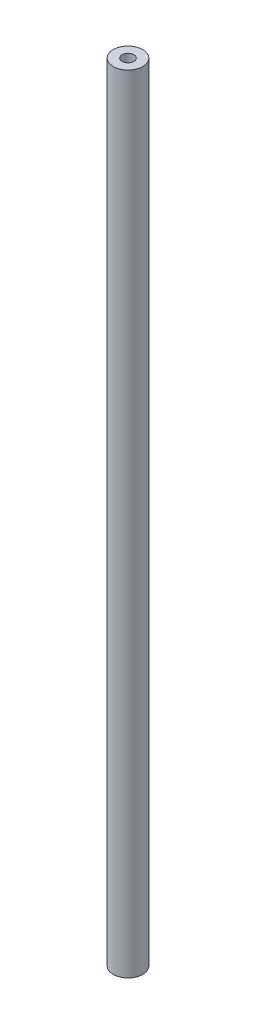
SolidWorks part; units mm, degrees
ref_plane "Front Plane" through (0, 0, 0) normal (0, 0, 1) x (1, 0, 0)
ref_plane "Top Plane" through (0, 0, 0) normal (0, 1, 0) x (1, 0, 0)
ref_plane "Right Plane" through (0, 0, 0) normal (1, 0, 0) x (0, 0, -1)
sketch "Sketch1" plane through (0, 0, 0) normal (0, 1, 0) x (1, 0, 0)
  circle A0 centre (0, 0) radius 4.7625
extrude "Boss-Extrude1" add sketch "Sketch1" along normal blind 254
sketch "Sketch2" plane through (0, 254, 0) normal (0, 1, 0) x (1, 0, 0)
  point P0 (0, 0)
hole_wizard "#10-24 Tapped Hole1" positions "3DSketch1" profile "Sketch3" tap size "#10-24" standard "Ansi Inch"
sketch3d "3DSketch1"
  circle A0 centre (0, 0, 0) radius 4.7625 construction
  point P0 (0, 254, 0)
  point P26 (0, 0, 0)
  point P29 (0, 0, 0)
  point P34 (0, 4.7625, 0)
  dimension "D1" = 0
sketch "Sketch3" plane through (0, 254, 0) normal (1, 0, 0) x (0, 0, 1)
  line L0 (0, 0) -> (0, 13.9708)
  line L1 (0, 13.9708) -> (1.8986, 12.83)
  line L2 (1.8986, 12.83) -> (1.8986, 0)
  line L5 (1.8986, 0) -> (0, 0)
  line L10 (0, 13.9708) -> (-1.8987, 12.83) construction
  line L11 (0, -6.35) -> (0, 107.95) construction
  dimension "Tap Drill Dia." = 3.7973
  dimension "Tap Drill Depth" = 12.83
  dimension "Drill Angle" = 118
cosmetic thread "Hole Thread1" parameters "D1"=9.65, "D2"=4.826
cosmetic thread "Hole Thread2" parameters "D1"=9.65, "D2"=4.826
cosmetic thread "Hole Thread3" parameters "D1"=9.65, "D2"=4.826
